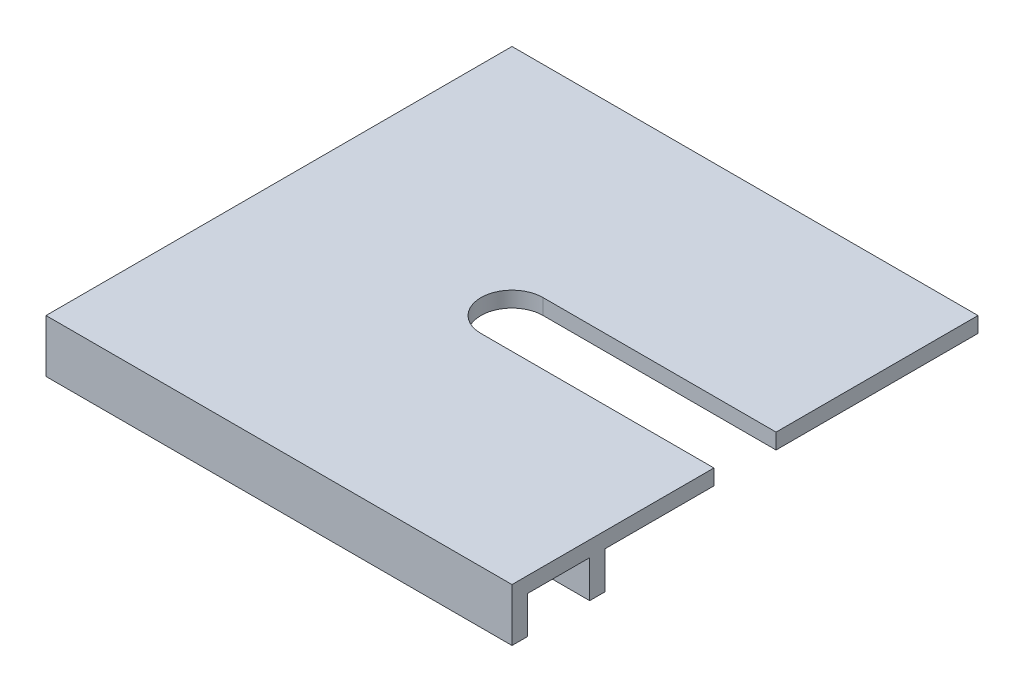
SolidWorks part; units mm, degrees
ref_plane "Front Plane" through (0, 0, 0) normal (0, 0, 1) x (1, 0, 0)
ref_plane "Top Plane" through (0, 0, 0) normal (0, 1, 0) x (1, 0, 0)
ref_plane "Right Plane" through (0, 0, 0) normal (1, 0, 0) x (0, 0, -1)
sketch "Sketch1" plane through (0, 0, 0) normal (0, 1, 0) x (1, 0, 0)
  line L0 (30, 26) -> (60, 26)
  line L1 (0, 0) -> (60, 0)
  line L2 (0, 0) -> (0, 60)
  line L3 (0, 60) -> (60, 60)
  line L4 (60, 0) -> (60, 60)
  line L5 (60, 26) -> (60, 34)
  line L6 (60, 34) -> (30, 34)
  line L7 (30, 60) -> (30, 0) construction
  line L8 (0, 30) -> (60, 30) construction
  circle A1 centre (30, 30) radius 4
  dimension "D2" = 8
  dimension "D1" = 60
extrude "Boss-Extrude1" add sketch "Sketch1" along normal blind 2 contours A1 L6 L4 L3 L2 L1 L0
sketch "Sketch2" plane through (0, 0, 0) normal (0, -1, 0) x (1, 0, 0)
  line L0 (60, 0) -> (0, 0)
  line L1 (0, 0) -> (0, -60)
  line L2 (0, -60) -> (12, -60)
  line L3 (0, -60) -> (60, -60) construction
  line L4 (12, -60) -> (12, -12)
  line L5 (12, -12) -> (60, -12)
  line L6 (60, 0) -> (60, -26) construction
  line L7 (60, 0) -> (60, -12)
  line L10 (35, -3.4387) -> (60, -2)
  line L11 (60, -2) -> (2, -2)
  line L12 (2, -2) -> (2, -60)
  line L13 (2, -60) -> (2.9356, -60)
  line L14 (60, -6) -> (0, -6) construction
  line L15 (6, -60) -> (6, 0) construction
  line L16 (60, -10) -> (2, -10)
  line L17 (10, -2) -> (10, -60)
  line M19 (60, -26) -> (60, 0)
  line M20 (60, 0) -> (0, 0)
  line M21 (0, 0) -> (0, -60)
  line M22 (0, -60) -> (60, -60)
  dimension "D1" = 12
  dimension "D2" = 8
  dimension "D3" = 8
extrude "Boss-Extrude2" add sketch "Sketch2" along normal blind 5 contours L16 L17 L2 L4 L5 M19 | L12 L11 M19 M20 M21 M22
chamfer "Chamfer1" distance 0.2 angle 45 12 edges at (1, -5, -60) (0, -5, -30) (30, -5, 0) (60, -5, -1) (31, -5, -2) (2, -5, -31) (60, -5, -11) (36, -5, -12) (12, -5, -36) (11, -5, -60) (10, -5, -35) (35, -5, -10)
